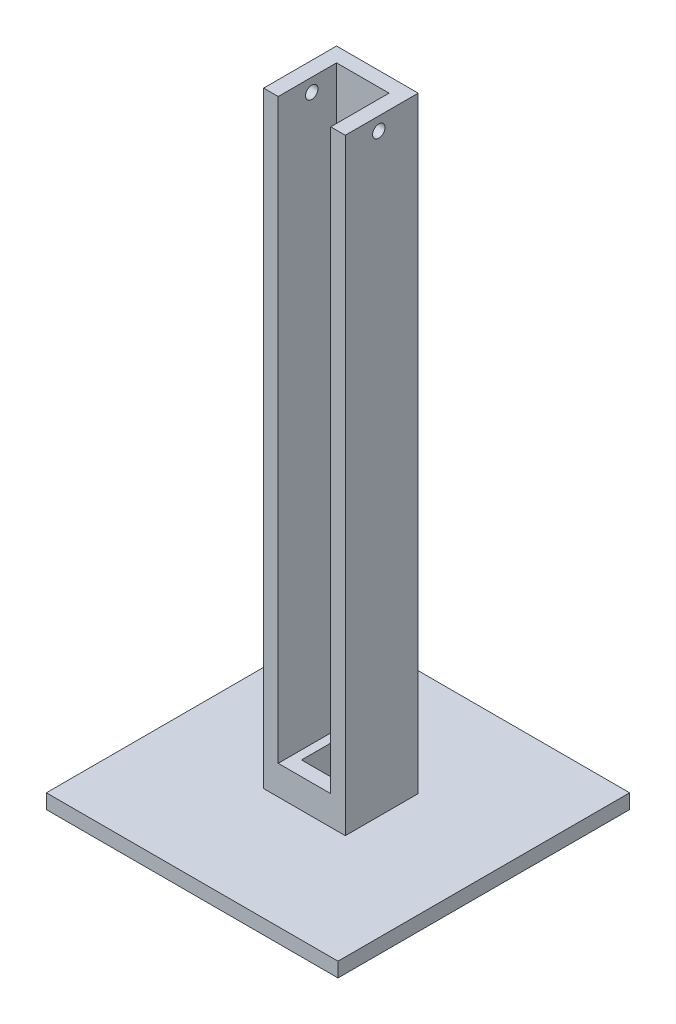
SolidWorks part; units mm, degrees
ref_plane "Front Plane" through (0, 0, 0) normal (0, 0, 1) x (1, 0, 0)
ref_plane "Top Plane" through (0, 0, 0) normal (0, 1, 0) x (1, 0, 0)
ref_plane "Right Plane" through (0, 0, 0) normal (1, 0, 0) x (0, 0, -1)
sketch "Sketch3" plane through (0, 0, 0) normal (0, 1, 0) x (1, 0, 0)
  line L3 (9, 8.5) -> (-9, 8.5)
  line L4 (9, -11.5) -> (9, 8.5)
  line L5 (-9, 8.5) -> (-9, -11.5)
  line L6 (14, -11.5) -> (14, 13.5)
  line L7 (14, 13.5) -> (-14, 13.5)
  line L8 (-14, 13.5) -> (-14, -11.5)
  line L9 (14, -11.5) -> (9, -11.5)
  line L10 (-9, -11.5) -> (-14, -11.5)
  dimension "D2" = 20
  dimension "D3" = 18
  dimension "D4" = 8.5
  dimension "D5" = 9
  dimension "D1" = 5
extrude "Boss-Extrude2" add sketch "Sketch3" against normal blind 208 separate body
sketch "Sketch5" plane through (14, 0, 0) normal (1, 0, 0) x (0, 0, -1)
  line L1 (13.5, -208) -> (13.5, 0) construction
  line L3 (-11.5, 0) -> (13.5, 0) construction
  circle A0 centre (0, -4.5) radius 2.125
  dimension "D1" = 4.5
  dimension "D2" = 13.5
extrude "Cut-Extrude1" cut sketch "Sketch5" against normal up to surface (28 mm away) up to face at (-14, -104, -1)
sketch "Sketch6" plane through (0, -208, 0) normal (0, -1, 0) x (1, 0, 0)
  line L0 (-50, -50) -> (50, -50)
  line L1 (-50, -50) -> (-50, 50)
  line L2 (50, -50) -> (50, 50)
  line L3 (-50, 50) -> (50, 50)
  line L4 (-50, -50) -> (50, 50) construction
  line L5 (50, -50) -> (-50, 50) construction
  point P1 (0, 0)
  dimension "D1" = 100
  dimension "D2" = 100
extrude "Boss-Extrude5" add sketch "Sketch6" along normal blind 5
sketch "Sketch7" plane through (0, -208, 0) normal (0, 1, 0) x (1, 0, 0)
  line L0 (-9, -11.5) -> (-9, 8.5) construction
  line L1 (-9, 8.5) -> (9, 8.5) construction
  circle A0 centre (0, 0) radius 4.5
  dimension "D1" = 9
  dimension "D2" = 8.5
extrude "Cut-Extrude2" cut sketch "Sketch7" against normal up to next
sketch "Sketch8" plane through (0, -208, 0) normal (0, 1, 0) x (1, 0, 0)
  line L3 (-9, 11.5) -> (9, 11.5)
  line L4 (-9, -11.5) -> (-9, 11.5)
  line L5 (9, 11.5) -> (9, -11.5)
  line L6 (-6, 9) -> (6, 9)
  line L7 (-6, -6.5) -> (-6, 9)
  line L8 (6, 9) -> (6, -6.5)
  line L9 (-9, -11.5) -> (9, -11.5)
  line L11 (-6, -6.5) -> (6, -6.5)
  line L12 (-6, -11.5) -> (-6, 11.5) construction
  line L13 (-9, -11.5) -> (-9, 11.5) construction
  line L14 (-9, 9) -> (9, 9) construction
  line L15 (6, 11.5) -> (6, -14.5) construction
  line L16 (9, 11.5) -> (9, -14.5) construction
  circle A0 centre (0, 0) radius 4.5 construction
  dimension "D5" = 6.5
  dimension "D3" = 23
  dimension "D1" = 2.5
  dimension "D2" = 3
extrude "Boss-Extrude6" add sketch "Sketch8" along normal blind 10
fillet "Fillet2" [suppressed] radius 10
sketch "Sketch10" plane through (0, -213, 0) normal (0, -1, 0) x (1, 0, 0)
  circle A0 centre (0, 0) radius 4.5 construction
  circle A1 centre (0, 0) radius 4.5
  circle A2 centre (0, 0) radius 4.8
  dimension "D1" = 0.3
extrude "Cut-Extrude7" cut sketch "Sketch10" against normal up to surface (5 mm away) up to face at (0, -208, -1)
